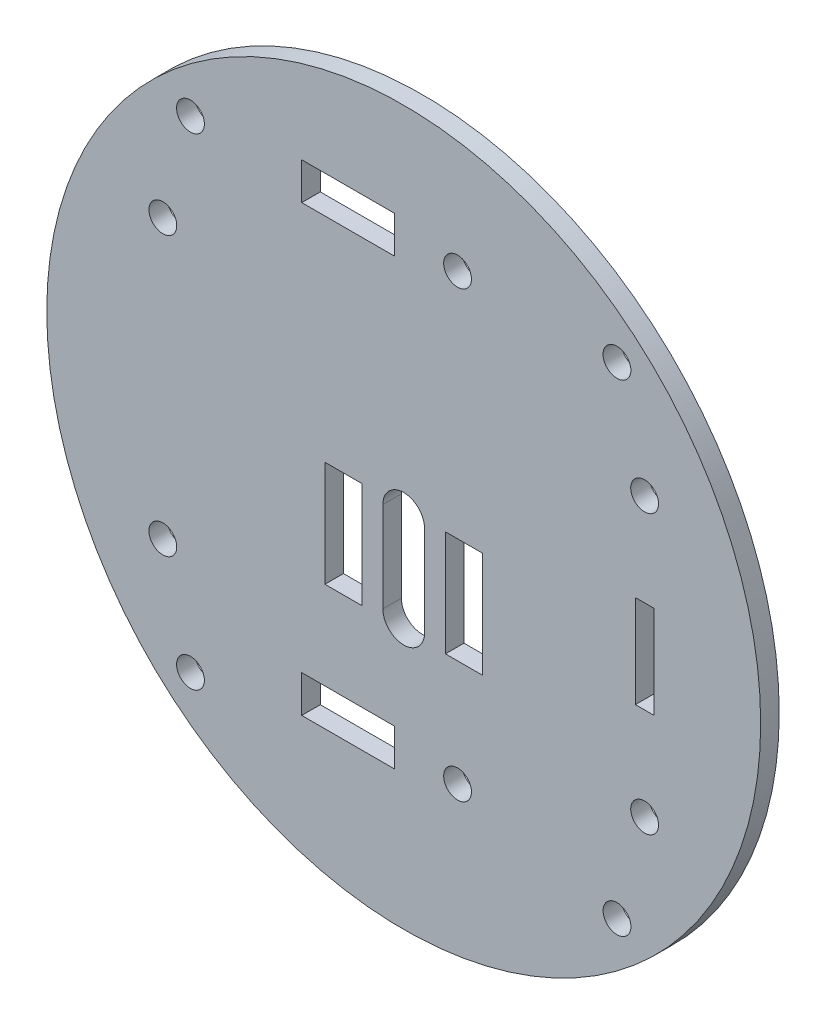
SolidWorks part; units mm, degrees
material "Acrylic (Medium-high impact)"
ref_plane "Front Plane" through (0, 0, 0) normal (0, 0, 1) x (1, 0, 0)
ref_plane "Top Plane" through (0, 0, 0) normal (0, 1, 0) x (1, 0, 0)
ref_plane "Right Plane" through (0, 0, 0) normal (1, 0, 0) x (0, 0, -1)
sketch "Model" plane through (0, 0, 0) normal (0, 0, 1) x (1, 0, 0)
  line L72 (2092.9945, 1156.4865) -> (2102.9945, 1156.4865)
  line L73 (2102.9945, 1112.5865) -> (2092.9945, 1112.5865)
  line L88 (2102.9945, 1156.4865) -> (2102.9945, 1160.4865)
  line L89 (2102.9945, 1160.4865) -> (2092.9945, 1160.4865)
  line L90 (2092.9945, 1160.4865) -> (2092.9945, 1156.4865)
  line L91 (2102.9945, 1112.5865) -> (2102.9945, 1108.5865)
  line L92 (2102.9945, 1108.5865) -> (2092.9945, 1108.5865)
  line L93 (2092.9945, 1112.5865) -> (2092.9945, 1108.5865)
  line L109 (2099.4945, 1133.4865) -> (2099.4945, 1122.0865)
  line L110 (2108.4945, 1133.4865) -> (2108.4945, 1122.0865)
  line L311 (2101.7445, 1132.6599) -> (2101.7445, 1122.9131)
  line L312 (2106.2445, 1132.6599) -> (2106.2445, 1122.9131)
  line L585 (2130.9769, 1137.5865) -> (2130.9769, 1127.5865)
  line L586 (2128.9769, 1127.5865) -> (2128.9769, 1137.5865)
  line L587 (2128.9769, 1127.5865) -> (2130.9769, 1127.5865)
  line L588 (2128.9769, 1137.5865) -> (2130.9769, 1137.5865)
  line L589 (2108.4945, 1133.4865) -> (2112.4945, 1133.4865)
  line L590 (2108.4945, 1122.0865) -> (2112.4945, 1122.0865)
  line L591 (2112.4945, 1122.0865) -> (2112.4945, 1133.4865)
  line L592 (2099.4945, 1133.4865) -> (2095.4945, 1133.4865)
  line L593 (2095.4945, 1133.4865) -> (2095.4945, 1122.0865)
  line L594 (2095.4945, 1122.0865) -> (2099.4945, 1122.0865)
  circle A29 centre (2103.9945, 1132.5865) radius 38.5
  circle A30 centre (2078.0137, 1147.5865) radius 1.5
  circle A31 centre (2129.9752, 1147.5865) radius 1.5
  circle A32 centre (2129.9752, 1117.5865) radius 1.5
  circle A33 centre (2078.0137, 1117.5865) radius 1.5
  circle A34 centre (2109.8005, 1158.4865) radius 1.5
  circle A35 centre (2109.8005, 1110.5865) radius 1.5
  circle A36 centre (2080.9945, 1106.6057) radius 1.5
  circle A37 centre (2080.9945, 1158.5673) radius 1.5
  circle A38 centre (2126.9945, 1106.6057) radius 1.5
  circle A39 centre (2126.9945, 1158.5673) radius 1.5
  arc A133 (2106.2445, 1132.6599) -> (2101.7445, 1132.6599) centre (2103.9945, 1132.6599) ccw
  arc A134 (2101.7445, 1122.9131) -> (2106.2445, 1122.9131) centre (2103.9945, 1122.9131) ccw
extrude "Boss-Extrude1" add sketch "Model" along normal blind 2
